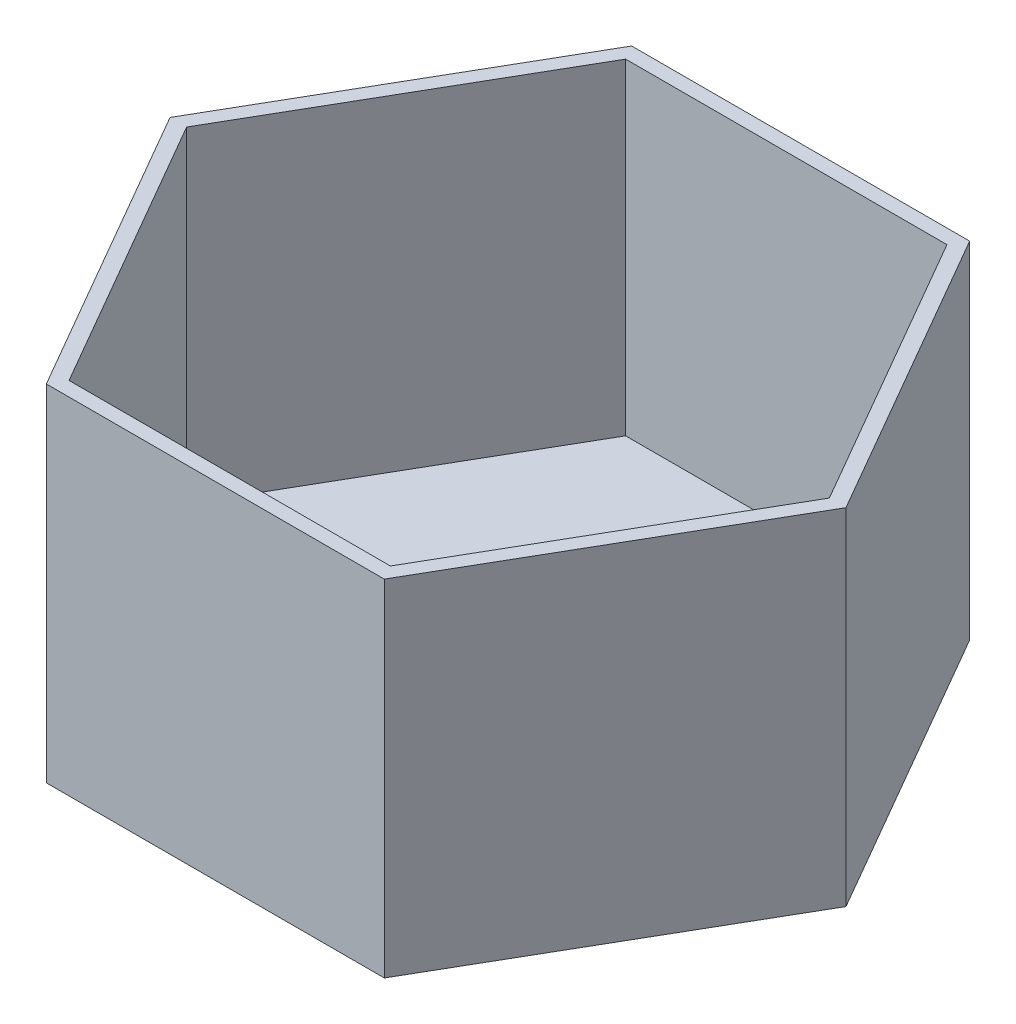
SolidWorks part; units mm, degrees
ref_plane "Front Plane" through (0, 0, 0) normal (0, 0, 1) x (1, 0, 0)
ref_plane "Top Plane" through (0, 0, 0) normal (0, 1, 0) x (1, 0, 0)
ref_plane "Right Plane" through (0, 0, 0) normal (1, 0, 0) x (0, 0, -1)
sketch "Sketch2" plane through (0, 0, 0) normal (0, 1, 0) x (1, 0, 0)
  line L1 (70.4367, 0) -> (35.2184, 61)
  line L2 (35.2184, 61) -> (-35.2184, 61)
  line L3 (-35.2184, 61) -> (-70.4367, 0)
  line L4 (-70.4367, 0) -> (-35.2184, -61)
  line L5 (-35.2184, -61) -> (35.2184, -61)
  line L6 (35.2184, -61) -> (70.4367, 0)
  circle A0 centre (0, 0) radius 61 construction
  dimension "D1" = 122
extrude "Boss-Extrude1" add sketch "Sketch2" along normal blind 72
sketch "Sketch3" plane through (0, 72, 0) normal (0, 1, 0) x (1, 0, 0)
  line L0 (70.4367, 0) -> (35.2184, 61) construction
  line L1 (66.9726, 0) -> (33.4863, 58)
  line L2 (33.4863, 58) -> (-33.4863, 58)
  line L3 (-33.4863, 58) -> (-66.9726, 0)
  line L4 (-66.9726, 0) -> (-33.4863, -58)
  line L5 (-33.4863, -58) -> (33.4863, -58)
  line L6 (33.4863, -58) -> (66.9726, 0)
  circle A0 centre (0, 0) radius 58 construction
  dimension "D1" = 3
extrude "Cut-Extrude1" cut sketch "Sketch3" against normal blind 68
sketch "Sketch4" plane through (0, 4, 0) normal (0, 1, 0) x (1, 0, 0)
  circle A0 centre (0, 0) radius 27.5
  dimension "D1" = 55
extrude "Boss-Extrude2" add sketch "Sketch4" along normal blind 5
